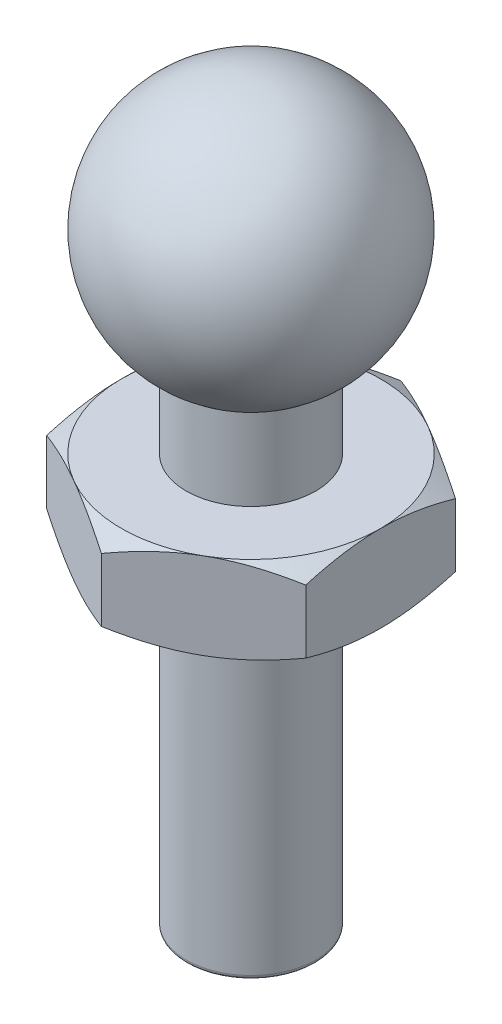
SolidWorks part; units mm, degrees
ref_plane "Front Plane" through (0, 0, 0) normal (0, 0, 1) x (1, 0, 0)
ref_plane "Top Plane" through (0, 0, 0) normal (0, 1, 0) x (1, 0, 0)
ref_plane "Right Plane" through (0, 0, 0) normal (1, 0, 0) x (0, 0, -1)
sketch "Sketch1" plane through (0, 0, 0) normal (0, 0, 1) x (1, 0, 0)
  line L1 (0, 0) -> (1.5, 0)
  line L2 (1.5, 0) -> (1.5, 11.4019)
  line L3 (0, 0) -> (0, 8.5)
  line L4 (0, 8.5) -> (0, 17)
  circle A0 centre (0, 14) radius 3 construction
  arc A1 (0, 17) -> (1.5, 11.4019) centre (0, 14) cw
  dimension "D1" = 6
  dimension "D2" = 1.5
  dimension "D3" = 14
revolve "Revolve1" add sketch "Sketch1" angle 360 about L4
fillet "Fillet1" radius 0.1 1 edges at (1.5, 0, 0)
ref_plane "Plane1" through (0, 7.5, 0) normal (0, 1, 0) x (1, 0, 0)
sketch "Sketch3" plane through (0, 7.5, 0) normal (0, 1, 0) x (1, 0, 0)
  line L1 (0, 3.4641) -> (-3, 1.7321)
  line L2 (-3, 1.7321) -> (-3, -1.7321)
  line L3 (-3, -1.7321) -> (0, -3.4641)
  line L4 (0, -3.4641) -> (3, -1.7321)
  line L5 (3, -1.7321) -> (3, 1.7321)
  line L6 (3, 1.7321) -> (0, 3.4641)
  circle A0 centre (0, 0) radius 3 construction
  circle A1 centre (0, 0) radius 1.5 construction
  circle A2 centre (0, 0) radius 1.5
  dimension "D1" = 6
extrude "Boss-Extrude1" add sketch "Sketch3" along normal blind 2
sketch "Sketch4" plane through (0, 7.5, 0) normal (0, -1, 0) x (1, 0, 0)
  circle A0 centre (0, 0) radius 3
extrude "Cut-Extrude3" cut sketch "Sketch4" against normal blind 2 draft 60 flip side to cut
sketch "Sketch5" plane through (0, 9.5, 0) normal (0, 1, 0) x (1, 0, 0)
  circle A0 centre (0, 0) radius 3
extrude "Cut-Extrude4" cut sketch "Sketch5" against normal blind 2 draft 60 flip side to cut
